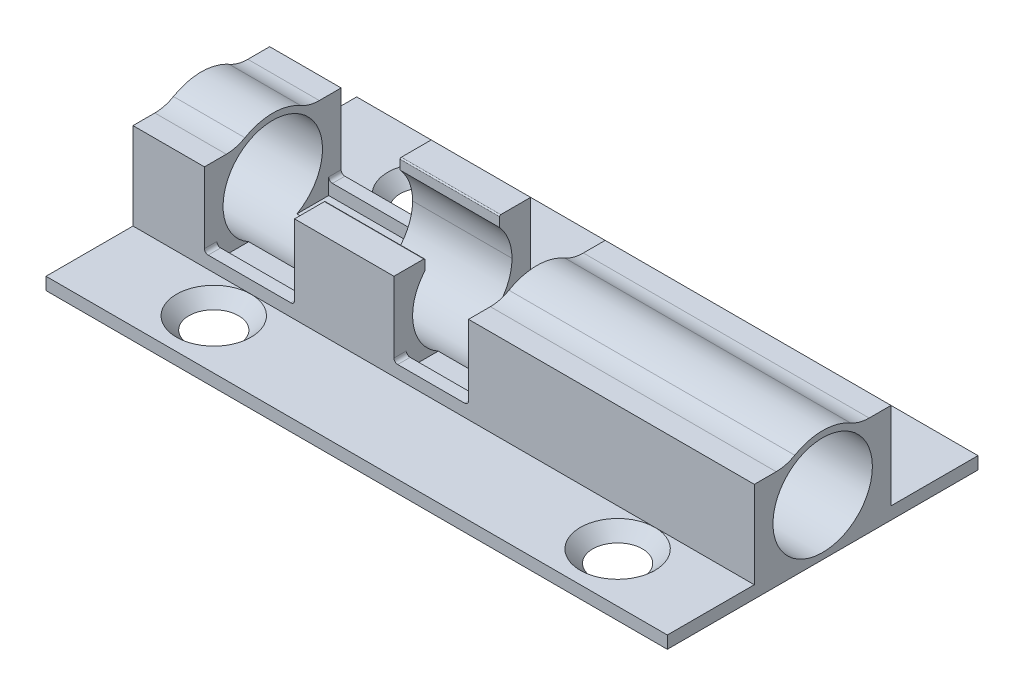
SolidWorks part; units mm, degrees
ref_plane "Front Plane" through (0, 0, 0) normal (0, 0, 1) x (1, 0, 0)
ref_plane "Top Plane" through (0, 0, 0) normal (0, 1, 0) x (1, 0, 0)
ref_plane "Right Plane" through (0, 0, 0) normal (1, 0, 0) x (0, 0, -1)
sketch "Sketch1" plane through (0, 0, 0) normal (0, 1, 0) x (1, 0, 0)
  line L1 (0, 0) -> (50, 0)
  line L2 (0, 0) -> (0, 25)
  line L3 (0, 25) -> (50, 25)
  line L4 (50, 0) -> (50, 25)
  dimension "D1" = 50
  dimension "D2" = 25
extrude "Boss-Extrude1" add sketch "Sketch1" along normal blind 1
sketch "Sketch4" plane through (0, 1, 0) normal (0, 1, 0) x (1, 0, 0)
  line L5 (50, 0) -> (50, 25) construction
  line L7 (0, 18) -> (50, 18)
  line L8 (0, 18) -> (0, 7)
  line L9 (0, 7) -> (50, 7)
  line L10 (50, 18) -> (50, 7)
  dimension "D1" = 7
  dimension "D2" = 11
  dimension "D3" = 7
extrude "Boss-Extrude2" add sketch "Sketch4" along normal blind 7
sketch "Sketch11" plane through (50, 0, 0) normal (1, 0, 0) x (0, 0, -1)
  line L0 (7, 4.5) -> (18, 4.5) construction
  circle A0 centre (12.5, 4.5) radius 4.5
  dimension "D1" = 9
extrude "Boss-Extrude5" add sketch "Sketch11" against normal through all
sketch "Sketch12" plane through (50, 0, 0) normal (1, 0, 0) x (0, 0, -1)
  line L0 (7, 4.5) -> (18, 4.5) construction
  circle A0 centre (12.5, 4.5) radius 4
  dimension "D1" = 8
extrude "Cut-Extrude2" cut sketch "Sketch12" against normal through all
fillet "Fillet1" radius 3 2 edges at (25, 8, -9.6716) (25, 8, -15.3284)
sketch "Sketch17" plane through (0, 1, 0) normal (0, 1, 0) x (1, 0, 0)
  line L0 (50, 18) -> (0, 18) construction
  line L1 (21, 18) -> (27, 18)
  line L2 (21, 18) -> (21, 7)
  line L3 (21, 7) -> (27, 7)
  line L4 (27, 18) -> (27, 7)
  line L5 (0, 7) -> (50, 7) construction
  line L6 (50, 7) -> (50, 18) construction
  dimension "D1" = 23
  dimension "D2" = 29
extrude "Cut-Extrude4" cut sketch "Sketch17" along normal blind 41
sketch "Sketch23" plane through (0, 1, 0) normal (0, 1, 0) x (1, 0, 0)
  line L0 (21, 18) -> (0, 18) construction
  line L1 (7, 18) -> (13, 18)
  line L2 (7, 18) -> (7, 7)
  line L3 (7, 7) -> (13, 7)
  line L4 (13, 18) -> (13, 7)
  line L5 (0, 7) -> (21, 7) construction
  line L6 (21, 10.255) -> (21, 14.745) construction
  dimension "D1" = 8
  dimension "D2" = 6
extrude "Cut-Extrude5" cut sketch "Sketch23" along normal blind 10
sketch "Sketch24" plane through (0, 8, 0) normal (0, 1, 0) x (1, 0, 0)
  line L1 (13, 18) -> (21, 18)
  line L2 (13, 18) -> (13, 7)
  line L3 (13, 7) -> (21, 7)
  line L4 (21, 18) -> (21, 7)
extrude "Cut-Extrude6" cut sketch "Sketch24" along normal blind 8
sketch "Sketch25" plane through (0, 8, 0) normal (0, 1, 0) x (1, 0, 0)
  line L0 (13, 14.4365) -> (13, 18) construction
  line L1 (13, 15.4965) -> (21, 15.4965)
  line L2 (13, 15.4965) -> (13, 9.4965)
  line L3 (13, 9.4965) -> (21, 9.4965)
  line L4 (21, 15.4965) -> (21, 9.4965)
  line L5 (21, 7) -> (21, 10.5635) construction
  line L6 (21, 18) -> (13, 18) construction
  line L7 (13, 7) -> (21, 7) construction
  dimension "D1" = 6
  dimension "D2" = 2.5035
  dimension "D3" = 2.4965
extrude "Cut-Extrude7" cut sketch "Sketch25" against normal blind 2
fillet "Fillet4" radius 0.1 2 edges at (17, 8, -9.4965) (17, 8, -15.4965)
hole_wizard "CSK for M3 Oval Head Machine Screw1" positions "Sketch28" profile "Sketch27" countersink size "M3" standard "ANSI Metric" end condition through all
sketch "Sketch28" plane through (0, 1, 0) normal (0, 1, 0) x (1, 0, 0)
  line L1 (50, 0) -> (50, 7) construction
  line L2 (50, 18) -> (50, 25) construction
  line L3 (27, 7) -> (50, 7) construction
  line L4 (0, 7) -> (7, 7) construction
  line L5 (7, 18) -> (0, 18) construction
  line L6 (50, 18) -> (27, 18) construction
  point P0 (9.5, 4)
  point P2 (42, 4)
  point P4 (42, 21)
  point P6 (9.5, 21)
  dimension "D1" = 8
  dimension "D2" = 8
  dimension "D3" = 3
  dimension "D4" = 3
  dimension "D5" = 3
  dimension "D6" = 3
  dimension "D7" = 32.5
  dimension "D8" = 32.5
sketch "Sketch27" plane through (9.5, 1, -4) normal (1, 0, 0) x (0, 0, 1)
  line L0 (0, 0) -> (0, 1)
  line L1 (0, 1) -> (1.5, 1)
  line L2 (1.5, 1) -> (1.5, 1.5)
  line L3 (1.5, 1.5) -> (3, 0)
  line L5 (3, 0) -> (0, 0)
  line L6 (-1.5, 1.5) -> (-3, 0) construction
  line L11 (0, -6.35) -> (0, 107.95) construction
  dimension "Thru Hole Dia." = 3
  dimension "Thru Hole Depth" = 1
  dimension "Near C'Sink Dia." = 6
  dimension "Near C'Sink Angle" = 90
sketch "Sketch29" plane through (0, 1, 0) normal (0, 1, 0) x (1, 0, 0)
  line L0 (7, 10.5635) -> (7, 7) construction
  line L1 (7, 8) -> (13, 8)
  line L2 (7, 8) -> (7, 7)
  line L3 (7, 7) -> (13, 7)
  line L4 (13, 8) -> (13, 7)
  dimension "D1" = 1
extrude "Boss-Extrude9" add sketch "Sketch29" along normal blind 1
sketch "Sketch30" plane through (0, 1, 0) normal (0, 1, 0) x (1, 0, 0)
  line L0 (21, 7) -> (21, 9.3965) construction
  line L1 (21, 8) -> (27, 8)
  line L2 (21, 8) -> (21, 7)
  line L3 (21, 7) -> (27, 7)
  line L4 (27, 8) -> (27, 7)
  line L5 (27, 8.7583) -> (27, 7) construction
  line L6 (27, 7) -> (27, 10.5635) construction
  dimension "D1" = 1
extrude "Boss-Extrude10" add sketch "Sketch30" along normal blind 1
sketch "Sketch32" plane through (0, 1, 0) normal (0, 1, 0) x (1, 0, 0)
  line L0 (13, 14.4365) -> (13, 18) construction
  line L1 (7, 18) -> (13, 18)
  line L2 (7, 18) -> (7, 17)
  line L3 (7, 17) -> (13, 17)
  line L4 (13, 18) -> (13, 17)
  dimension "D1" = 1
extrude "Boss-Extrude11" add sketch "Sketch32" along normal blind 1
sketch "Sketch33" plane through (0, 1, 0) normal (0, 1, 0) x (1, 0, 0)
  line L0 (27, 18) -> (27, 16.2417) construction
  line L1 (21, 18) -> (27, 18)
  line L2 (21, 18) -> (21, 17)
  line L3 (21, 17) -> (27, 17)
  line L4 (27, 18) -> (27, 17)
  dimension "D1" = 1
extrude "Boss-Extrude12" add sketch "Sketch33" along normal blind 1
sketch "Sketch37" plane through (7, 0, 0) normal (1, 0, 0) x (0, 0, -1)
  line L0 (17, 1) -> (14.4365, 1) construction
  line L1 (8, 17) -> (17, 17)
  line L2 (8, 17) -> (8, 1)
  line L3 (8, 1) -> (17, 1)
  line L4 (17, 17) -> (17, 1)
  line L5 (8, 17) -> (17, 1) construction
  line L6 (8, 1) -> (17, 17) construction
  arc A0 (14.745, 8.4) -> (10.255, 8.4) centre (12.5, 4.5) ccw construction
  point P0 (12.5, 9)
extrude "Cut-Extrude10" cut sketch "Sketch37" against normal blind 1.25
sketch "Sketch41" plane through (7, 0, 0) normal (1, 0, 0) x (0, 0, -1)
  line L1 (7, 8) -> (8, 8)
  line L2 (7, 8) -> (7, 2)
  line L3 (7, 2) -> (8, 2)
  line L4 (8, 8) -> (8, 2)
extrude "Cut-Extrude12" cut sketch "Sketch41" against normal blind 1.25
sketch "Sketch42" plane through (7, 0, 0) normal (1, 0, 0) x (0, 0, -1)
  line L1 (17, 8) -> (18, 8)
  line L2 (17, 8) -> (17, 2)
  line L3 (17, 2) -> (18, 2)
  line L4 (18, 8) -> (18, 2)
extrude "Cut-Extrude13" cut sketch "Sketch42" against normal blind 1.25
fillet "Fillet5" radius 0.3 8 edges at (13, 2, -7.5) (13, 2, -17.5) (27, 2, -17.5) (27, 2, -7.5) (21, 2, -7.5) (21, 2, -17.5) (5.75, 2, -17.5) (5.75, 2, -7.5)
